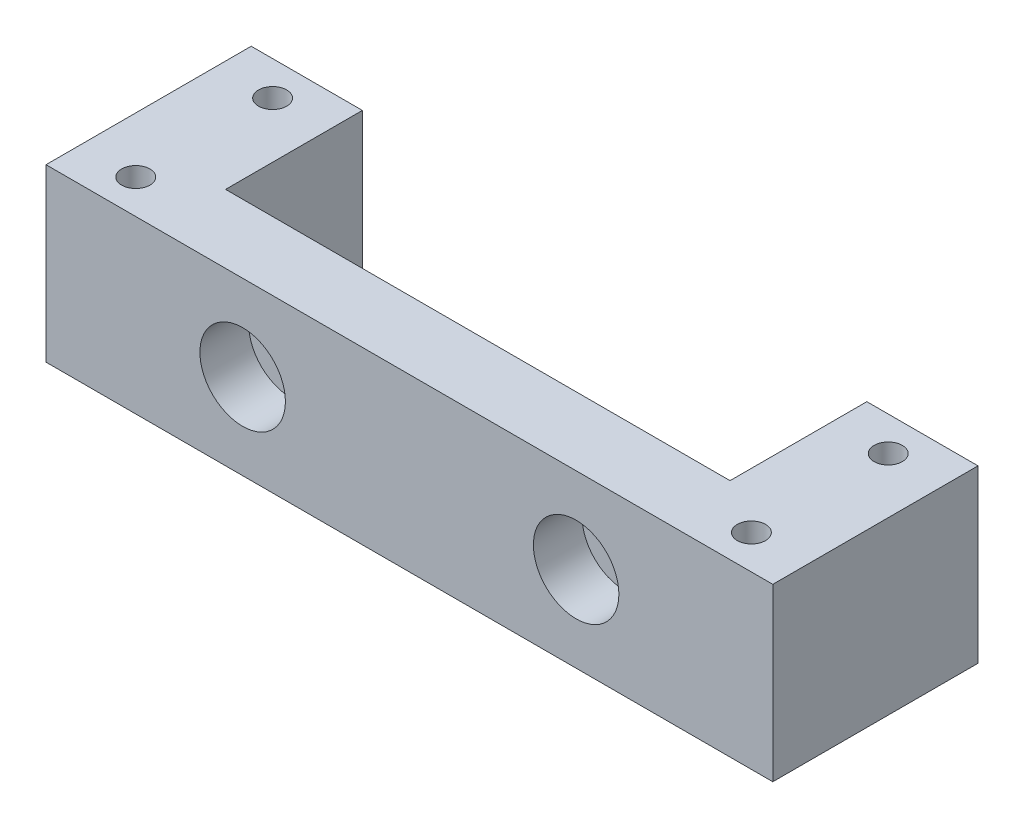
SolidWorks part; units mm, degrees
material "6061 合金"
ref_plane "前视基准面" through (0, 0, 0) normal (0, 0, 1) x (1, 0, 0)
ref_plane "上视基准面" through (0, 0, 0) normal (0, 1, 0) x (1, 0, 0)
ref_plane "右视基准面" through (0, 0, 0) normal (1, 0, 0) x (0, 0, -1)
sketch "草图1" plane through (0, 0, 0) normal (0, 1, 0) x (1, 0, 0)
  line L0 (0, 0) -> (0, 66.5142) construction
  line L1 (-42.5, 24) -> (-29.5, 24)
  line L2 (-42.5, 24) -> (-42.5, 0)
  line L3 (-42.5, 0) -> (42.5, 0)
  line L4 (42.5, 24) -> (42.5, 0)
  line L5 (-42.5, 24) -> (42.5, 0) construction
  line L6 (-42.5, 0) -> (42.5, 24) construction
  line L7 (29.5, 24) -> (42.5, 24)
  line L8 (-29.5, 8) -> (29.5, 8)
  line L9 (-29.5, 8) -> (-29.5, 24)
  line L11 (29.5, 8) -> (29.5, 24)
  line L12 (-29.5, 8) -> (29.5, 24) construction
  line L13 (-29.5, 24) -> (29.5, 8) construction
  point P0 (0, 12)
  point P8 (0, 16)
  dimension "D1" = 59
  dimension "D2" = 13
  dimension "D3" = 16
  dimension "D4" = 8
extrude "凸台-拉伸1" add sketch "草图1" along normal blind 20
hole_wizard "打孔尺寸(%根据)内六角圆柱头螺钉的类型0" positions "草图3" profile "草图2" counterbore size "M5" standard "GB" end condition up to next
sketch "草图3" plane through (0, 0, 0) normal (0, 0, 1) x (1, 0, 0)
  point P0 (19.5, 10)
  point P3 (-19.5, 10)
sketch "草图2" plane through (19.5, 10, 0) normal (1, 0, 0) x (0, -1, 0)
  line L0 (0, 0) -> (0, 8)
  line L1 (0, 8) -> (2.75, 8)
  line L3 (2.75, 8) -> (2.75, 5.7)
  line L4 (2.75, 5.7) -> (5, 5.7)
  line L5 (5, 5.7) -> (5, 0)
  line L7 (5, 0) -> (0, 0)
  line L11 (0, -6.35) -> (0, 107.95) construction
  dimension "通孔孔直径" = 5.5
  dimension "通孔孔深度" = 8
  dimension "柱形沉头孔直径" = 10
  dimension "柱形沉头孔深度" = 5.7
hole_wizard "M4 螺纹孔1" positions "草图5" profile "草图4" tap size "M4" standard "GB" end condition up to next
sketch "草图5" plane through (0, 0, 0) normal (0, -1, 0) x (-1, 0, 0)
  line L0 (0, 0) -> (0, 33.1875) construction
  line L4 (36, 24) -> (36, 5.9425) construction
  line L5 (29.5, 24) -> (42.5, 24) construction
  line L11 (42.5, 0) -> (-42.5, 0) construction
  point P0 (36, 4)
  point P2 (-36, 4)
  point P34 (36, 20)
  point P36 (-36, 20)
  dimension "D1" = 4
  dimension "D2" = 4
sketch "草图4" plane through (-36, 0, -4) normal (1, 0, 0) x (0, 0, -1)
  line L0 (0, 0) -> (0, 20)
  line L1 (0, 20) -> (1.65, 20)
  line L2 (1.65, 20) -> (1.65, 0)
  line L5 (1.65, 0) -> (0, 0)
  line L11 (0, -6.35) -> (0, 107.95) construction
  dimension "通孔螺纹孔钻头直径" = 3.3
  dimension "通孔螺纹孔钻头深度" = 20
cosmetic thread "孔螺蚊线1" parameters "D2"=4
cosmetic thread "孔螺蚊线2" parameters "D2"=4
cosmetic thread "孔螺蚊线3" parameters "D2"=4
cosmetic thread "孔螺蚊线4" parameters "D2"=4
